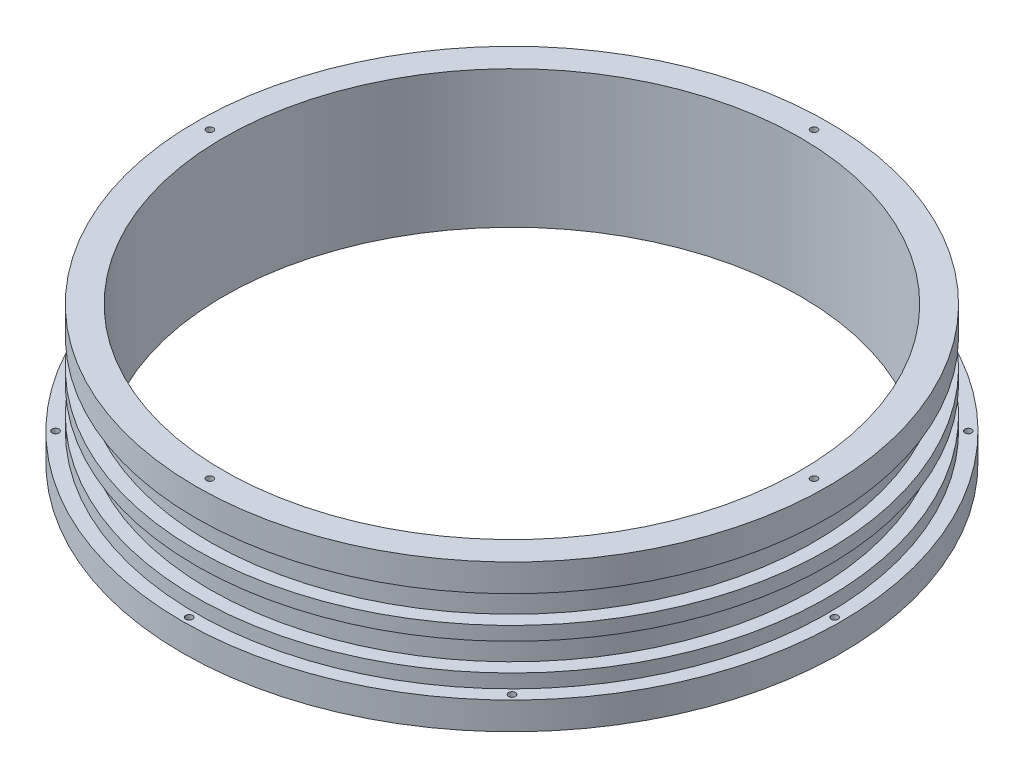
SolidWorks part; units mm, degrees
material "6061 Alloy"
ref_plane "Front Plane" through (0, 0, 0) normal (0, 0, 1) x (1, 0, 0)
ref_plane "Top Plane" through (0, 0, 0) normal (0, 1, 0) x (1, 0, 0)
ref_plane "Right Plane" through (0, 0, 0) normal (1, 0, 0) x (0, 0, -1)
sketch "Sketch2" plane through (0, 0, 0) normal (0, 1, 0) x (1, 0, 0)
  circle A0 centre (0, 0) radius 76.2
extrude "Boss-Extrude1" add sketch "Sketch2" along normal blind 6.35
sketch "Sketch3" plane through (0, 0, 0) normal (0, 1, 0) x (1, 0, 0)
  circle A0 centre (0, 0) radius 73.025
extrude "Boss-Extrude2" add sketch "Sketch3" along normal blind 9.525
sketch "Sketch4" plane through (0, 0, 0) normal (0, 1, 0) x (1, 0, 0)
  circle A0 centre (0, 0) radius 69.85
extrude "Boss-Extrude3" add sketch "Sketch4" along normal blind 15.875
sketch "Sketch6" plane through (0, 15.875, 0) normal (0, 1, 0) x (1, 0, 0)
  circle A0 centre (0, 0) radius 73.025
extrude "Boss-Extrude4" add sketch "Sketch6" along normal blind 3.175
sketch "Sketch7" plane through (0, 19.05, 0) normal (0, 1, 0) x (1, 0, 0)
  circle A0 centre (0, 0) radius 69.85
extrude "Boss-Extrude5" add sketch "Sketch7" along normal blind 6.35
sketch "Sketch8" plane through (0, 25.4, 0) normal (0, 1, 0) x (1, 0, 0)
  circle A0 centre (0, 0) radius 73.025
extrude "Boss-Extrude6" add sketch "Sketch8" along normal blind 6.35
sketch "Sketch9" plane through (0, 0, 0) normal (0, -1, 0) x (1, 0, 0)
  circle A0 centre (0, 0) radius 66.675
extrude "Cut-Extrude1" cut sketch "Sketch9" against normal through all
sketch "Sketch10" plane through (0, 6.35, 0) normal (0, 1, 0) x (1, 0, 0)
  circle A0 centre (0, 74.6125) radius 0.7937
  circle A1 centre (52.759, 52.759) radius 0.7937
  circle A2 centre (74.6125, 0) radius 0.7937
  circle A3 centre (52.759, -52.759) radius 0.7937
  circle A4 centre (0, -74.6125) radius 0.7937
  circle A5 centre (-52.759, -52.759) radius 0.7937
  circle A6 centre (-74.6125, 0) radius 0.7937
  circle A7 centre (-52.759, 52.759) radius 0.7937
  point P19 (0, 0)
  dimension "D1" = 8
extrude "Cut-Extrude2" cut sketch "Sketch10" against normal through all
sketch "Sketch11" plane through (0, 0, 0) normal (0, -1, 0) x (1, 0, 0)
  circle A0 centre (0, 0) radius 69.85
  circle A1 centre (0, 0) radius 73.025
extrude "Cut-Extrude3" cut sketch "Sketch11" against normal blind 3.175
sketch "Sketch12" plane through (0, 31.75, 0) normal (0, 1, 0) x (1, 0, 0)
  circle A0 centre (0, -69.85) radius 0.7937
  circle A1 centre (-69.85, 0) radius 0.7938
  circle A2 centre (0, 69.85) radius 0.7938
  circle A3 centre (69.85, 0) radius 0.7937
  point P11 (0, 0)
  dimension "D1" = 4
extrude "Cut-Extrude4" cut sketch "Sketch12" against normal blind 3.175
